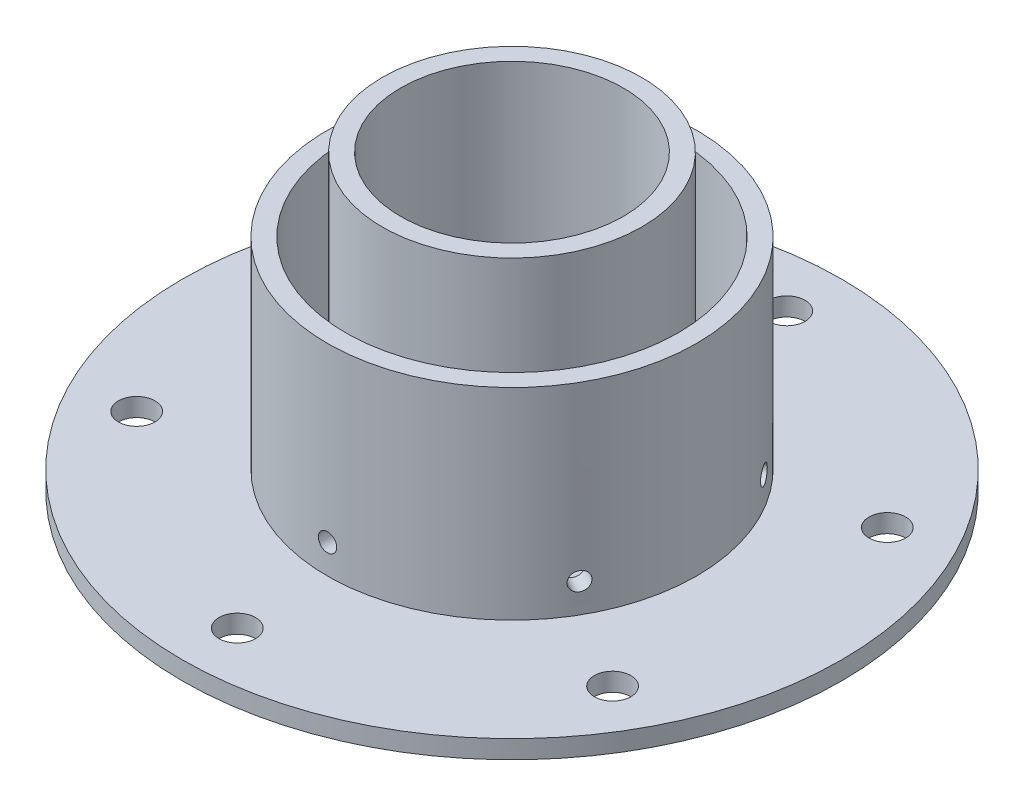
SolidWorks part; units mm, degrees
ref_plane "Front Plane" through (0, 0, 0) normal (0, 0, 1) x (1, 0, 0)
ref_plane "Top Plane" through (0, 0, 0) normal (0, 1, 0) x (1, 0, 0)
ref_plane "Right Plane" through (0, 0, 0) normal (1, 0, 0) x (0, 0, -1)
sketch "Sketch1" plane through (0, 0, 0) normal (0, 0, 1) x (1, 0, 0)
  line L3 (-3.175, 3.175) -> (-9.525, 3.175)
  line L6 (-9.525, 3.175) -> (-9.525, 38.1)
  line L7 (-9.525, 38.1) -> (-12.7, 38.1)
  line L8 (-12.7, 3.175) -> (-12.7, 38.1)
  line L10 (-3.175, 3.175) -> (-3.175, 50.8)
  line L11 (-3.175, 50.8) -> (0, 50.8)
  line L13 (0, 0) -> (0, 50.8)
  line L14 (0, 0) -> (-37.846, 0)
  line L16 (-3.175, 3.175) -> (-9.525, 3.175)
  line L17 (-37.846, 0) -> (-37.846, 3.175)
  line L18 (19.304, 0) -> (19.304, 50.8) construction
  line L19 (-12.7, 3.175) -> (-37.846, 3.175)
  dimension "D6" = 3.175
  dimension "D7" = 3.175
  dimension "D2" = 50.8
  dimension "D3" = 19.304
  dimension "D8" = 3.175
  dimension "D9" = 12.7
  dimension "D5" = 6.35
  dimension "D4" = 57.15
  dimension "D1" = 32.004
revolve "Revolve1" add sketch "Sketch1" angle 360 about L18
sketch "Sketch2" plane through (0, 0, 0) normal (0, 0, 1) x (1, 0, 0)
  line L0 (19.304, 38.1) -> (19.304, 3.175) construction
  line L1 (76.454, 3.175) -> (-37.846, 3.175) construction
  circle A0 centre (19.304, 8.255) radius 1.5875
  dimension "D1" = 3.175
  dimension "D2" = 5.08
extrude "Cut-Extrude1" cut sketch "Sketch2" along normal blind 32.512 from offset 25.4
pattern_circular "CirPattern1" count 6 over 360 about axis through (19.304, 0, 0) along (0, -1, 0) of "Cut-Extrude1"
sketch "Sketch3" plane through (0, 3.175, 0) normal (0, 1, 0) x (1, 0, 0)
  line L0 (19.304, 0) -> (19.304, 57.15) construction
  line L1 (-21.9405, 23.8125) -> (19.304, 0) construction
  circle A0 centre (-21.9405, 23.8125) radius 3.175
  circle A2 centre (19.304, 0) radius 47.625 construction
  circle A3 centre (19.304, 0) radius 22.479 construction
  circle A5 centre (19.304, 0) radius 57.15 construction
  dimension "D5" = 6.35
  dimension "D1" = 95.25
  dimension "D2" = 57.15
  dimension "D3" = 47.625
  dimension "D4" = 60
extrude "Cut-Extrude2" cut sketch "Sketch3" against normal blind 50.8
pattern_circular "CirPattern2" count 6 over 360 about axis through (19.304, 0, 0) along (0, 1, 0) of "Cut-Extrude2"
equation "\"ID\"= 3"
equation "\"boltDia\"= 1 / 4in"
equation "\"BHC\"= 5.5in"
equation "\"height\"= 2in"
equation "\"drainDia\"= 1 / 8in"
equation "\"outerDia\"= 4in"
equation "\"tubeDia\"= 1.5in"
equation "\"D2@Sketch1\"=\"height\""
equation "\"D3@Sketch1\"=1.52/2in"
equation "\"D5@Sketch3\"=\"boltDia\""
